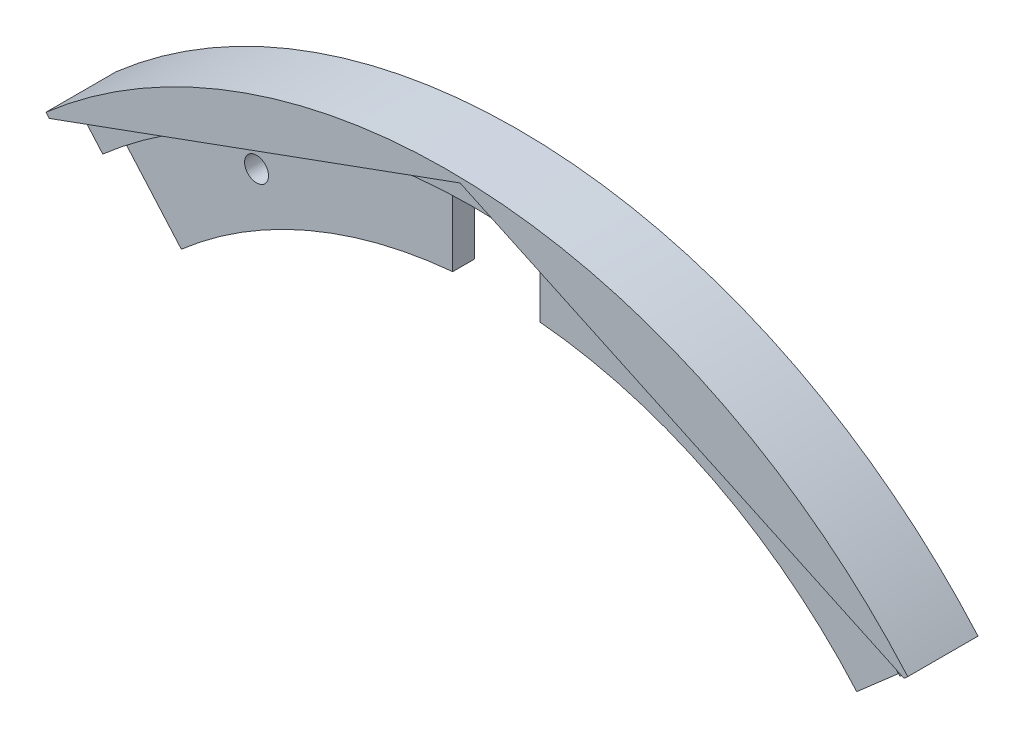
SolidWorks part; units mm, degrees
ref_plane "Front Plane" through (0, 0, 0) normal (0, 0, 1) x (1, 0, 0)
ref_plane "Top Plane" through (0, 0, 0) normal (0, 1, 0) x (1, 0, 0)
ref_plane "Right Plane" through (0, 0, 0) normal (1, 0, 0) x (0, 0, -1)
sketch "Sketch1" plane through (0, 0, 0) normal (0, 0, 1) x (1, 0, 0)
  line L0 (0, 284.5128) -> (0, -315.9314) construction
  line L1 (-464.297, 0) -> (544.589, 0) construction
  line L2 (2.7918, 138.8272) -> (104.5532, 91.375)
  line L9 (2.7918, 138.8272) -> (-91.375, 104.5532)
  line L11 (-138.8272, 2.7918) -> (-104.5532, -91.375)
  line L13 (-2.7918, -138.8272) -> (91.375, -104.5532)
  line L15 (138.8272, -2.7918) -> (104.5532, 91.375)
  line L17 (138.8272, -2.7918) -> (91.375, -104.5532)
  line L18 (-2.7918, -138.8272) -> (-104.5532, -91.375)
  line L19 (-138.8272, 2.7918) -> (-91.375, 104.5532)
  line L20 (103.344, 94.6973) -> (54.7291, 117.3669)
  line L21 (-117.3669, 54.7291) -> (-140.0364, 6.1141)
  line L22 (-103.344, -94.6973) -> (-54.7291, -117.3669)
  line L23 (94.6973, -103.344) -> (117.3669, -54.7291)
  circle A0 centre (0, 0) radius 129.5 construction
  circle A2 centre (0, 0) radius 129.5
  circle A3 centre (0, 0) radius 109.75
  dimension "D2" = 259
  dimension "D3" = 219.5
  dimension "D1" = 70
  dimension "D4" = 259
  dimension "D5" = 254
  dimension "D6" = 4
sketch "Sketch2" plane through (0, 0, 0) normal (0, 0, 1) x (1, 0, 0)
  circle A2 centre (0, 0) radius 109.75
  circle A3 centre (0, 0) radius 129.5
  point P1 (114.75, 0)
  point P3 (0, 0)
  point P9 (104.9544, 32.0878)
  dimension "D1" = 219.5
  dimension "D2" = 259
sketch "Sketch3" plane through (0, 0, 0) normal (0, 0, 1) x (1, 0, 0)
  line L0 (0, 216.6703) -> (0, -179.3029) construction
  line L2 (0, 284.5128) -> (0, -315.9314) construction
  line L4 (-261.0178, 0) -> (186.7113, 0) construction
  line L5 (-464.297, 0) -> (544.589, 0) construction
  line L22 (-157.8941, 129.5) -> (159.8749, 129.5) construction
  line L23 (0, 0) -> (-64.3319, 176.7503) construction
  line L40 (-132.8743, 89.4487) -> (56.0531, 158.2127) construction
  line L41 (129.5, -10) -> (109.5, -10)
  line L42 (10, 129.5) -> (-10, 129.5)
  line L43 (10, 129.5) -> (10, 109.5)
  line L44 (10, 109.5) -> (-10, 109.5)
  line L45 (-10, 129.5) -> (-10, 109.5)
  line L46 (129.5, -10) -> (129.5, 10)
  line L47 (129.5, 10) -> (109.5, 10)
  line L48 (109.5, -10) -> (109.5, 10)
  line L49 (-10, -129.5) -> (-10, -109.5)
  line L50 (-10, -129.5) -> (10, -129.5)
  line L51 (10, -129.5) -> (10, -109.5)
  line L52 (-10, -109.5) -> (10, -109.5)
  line L53 (-129.5, 10) -> (-109.5, 10)
  line L54 (-129.5, 10) -> (-129.5, -10)
  line L55 (-129.5, -10) -> (-109.5, -10)
  line L56 (-109.5, 10) -> (-109.5, -10)
  line L57 (-62.4545, 104.4377) -> (46.2898, 144.0174) construction
  circle A8 centre (-54.9668, 107.163) radius 2.75
  circle A9 centre (-26.776, 117.4236) radius 2.75
  circle A10 centre (107.163, 54.9668) radius 2.75
  circle A11 centre (117.4236, 26.776) radius 2.75
  circle A12 centre (54.9668, -107.163) radius 2.75
  circle A13 centre (26.776, -117.4236) radius 2.75
  circle A14 centre (-107.163, -54.9668) radius 2.75
  circle A15 centre (-117.4236, -26.776) radius 2.75
  dimension "D8" = 5.5
  dimension "D9" = 15
  dimension "D1" = 129.5
  dimension "D2" = 20
  dimension "D3" = 70
  dimension "D4" = 129.5
  dimension "D5" = 20
  dimension "D7" = 10
  dimension "D6" = 20
  dimension "D10" = 10
  dimension "D12" = 4
  dimension "D11" = 4
sketch "Sketch4" plane through (0, 0, 0) normal (0, 0, 1) x (1, 0, 0)
  line L0 (0, 247.7886) -> (0, -153.99) construction
  line L1 (0, 284.5128) -> (0, -315.9314) construction
  line L2 (-190.7853, 0) -> (227.3701, 0) construction
  line L3 (-464.297, 0) -> (544.589, 0) construction
  line L4 (2.7918, 138.8272) -> (104.5532, 91.375) construction
  line L5 (2.7918, 138.8272) -> (-91.375, 104.5532) construction
  line L6 (2.7918, 138.8272) -> (104.5532, 91.375)
  line L7 (2.7918, 138.8272) -> (-91.375, 104.5532)
  line L8 (0, 0) -> (-91.375, 104.5532) construction
  line L9 (0, 0) -> (104.5532, 91.375) construction
  line L10 (104.5532, 91.375) -> (105.4152, 92.1284)
  line L11 (-91.375, 104.5532) -> (-92.1284, 105.4152)
  arc A1 (105.4152, 92.1284) -> (-92.1284, 105.4152) centre (0, 0) ccw
  dimension "D1" = 280
extrude "Boss-Extrude1" add sketch "Sketch4" along normal blind 6.1
sketch "Sketch5" plane through (0, 0, 0) normal (0, 0, 1) x (1, 0, 0)
  line L0 (0, 161.9102) -> (0, -158.9824) construction
  line L1 (0, 284.5128) -> (0, -315.9314) construction
  line L6 (2.7918, 138.8272) -> (104.5532, 91.375) construction
  line L7 (30.7222, 125.803) -> (76.6229, 104.3992)
  line L8 (-92.1284, 105.4152) -> (-85.2187, 97.5091)
  line L9 (97.5091, 85.2187) -> (105.4152, 92.1284)
  arc A0 (97.5091, 85.2187) -> (76.6229, 104.3992) centre (0, 0) ccw
  arc A2 (30.7222, 125.803) -> (-85.2187, 97.5091) centre (0, 0) ccw
  arc A3 (105.4152, 92.1284) -> (-92.1284, 105.4152) centre (0, 0) ccw construction
  arc A4 (105.4152, 92.1284) -> (-92.1284, 105.4152) centre (0, 0) ccw
  dimension "D1" = 259
extrude "Boss-Extrude4" add sketch "Sketch5" against normal blind 5
sketch "Sketch6" plane through (0, 0, -5) normal (0, 0, -1) x (-1, 0, 0)
  line L2 (0, 169.5523) -> (0, -199.0298) construction
  line L3 (0, 284.5128) -> (0, -315.9314) construction
  line L4 (-232.6153, 0) -> (198.4747, 0) construction
  line L5 (464.297, 0) -> (-544.589, 0) construction
  line L6 (-10, 129.5) -> (10, 129.5) construction
  line L7 (-10, 129.5) -> (10, 129.5)
  line L8 (-10, 129.5) -> (-10, 109.2684)
  line L9 (10, 129.5) -> (10, 109.2684)
  line L10 (92.1284, 105.4152) -> (72.2056, 82.6192)
  line L11 (-82.6192, 72.2056) -> (-105.4152, 92.1284)
  arc A0 (92.1284, 105.4152) -> (-105.4152, 92.1284) centre (0, 0) ccw construction
  arc A1 (92.1284, 105.4152) -> (-105.4152, 92.1284) centre (0, 0) ccw
  arc A2 (72.2056, 82.6192) -> (10, 109.2684) centre (0, 0) ccw
  circle A3 centre (54.9668, 107.163) radius 2.75 construction
  circle A4 centre (54.9668, 107.163) radius 2.75
  arc A5 (-10, 109.2684) -> (-82.6192, 72.2056) centre (0, 0) ccw
  dimension "D1" = 219.45
extrude "Boss-Extrude5" add sketch "Sketch6" along normal blind 5
sketch "Sketch7" plane through (0, 0, 0) normal (0, 0, 1) x (1, 0, 0)
  line L0 (0, 0) -> (94.5697, 112.7038) construction
  line L1 (-464.297, 0) -> (544.589, 0) construction
  circle A0 centre (76.8131, 91.5423) radius 2.75
  dimension "D2" = 5.5
  dimension "D3" = 119.5
  dimension "D1" = 50
extrude "Cut-Extrude1" cut sketch "Sketch7" against normal through all
